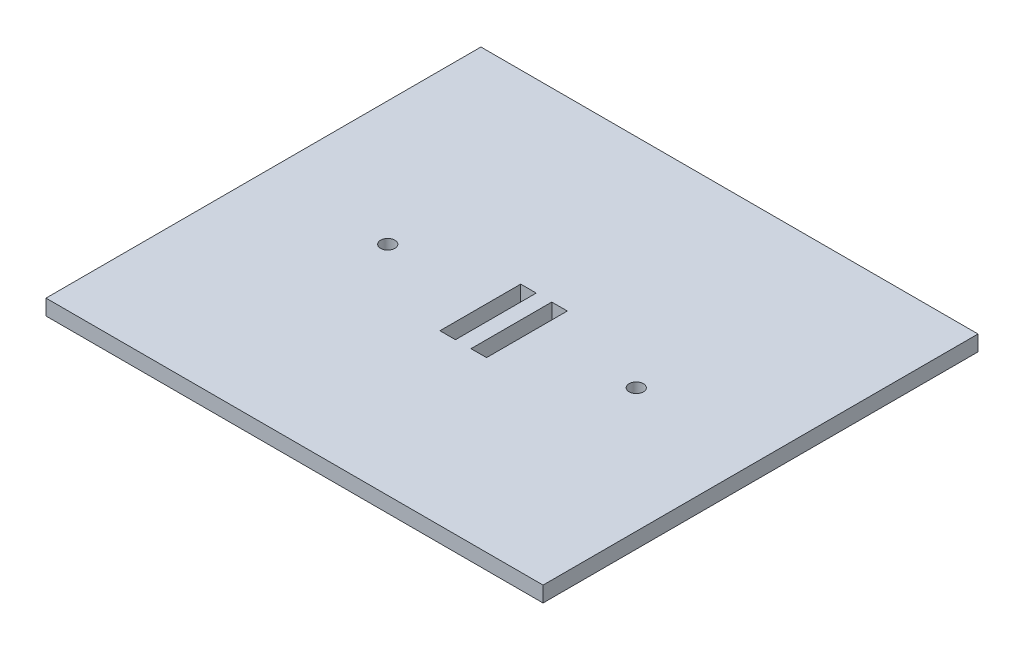
SolidWorks part; units mm, degrees
ref_plane "Front Plane" through (0, 0, 0) normal (0, 0, 1) x (1, 0, 0)
ref_plane "Top Plane" through (0, 0, 0) normal (0, 1, 0) x (1, 0, 0)
ref_plane "Right Plane" through (0, 0, 0) normal (1, 0, 0) x (0, 0, -1)
sketch "Sketch2" plane through (0, 0, 0) normal (0, 1, 0) x (1, 0, 0)
  line L2 (-50.8, -44.45) -> (50.8, -44.45)
  line L3 (-50.8, -44.45) -> (-50.8, 44.45)
  line L4 (-50.8, 44.45) -> (50.8, 44.45)
  line L5 (50.8, -44.45) -> (50.8, 44.45)
  line L6 (-50.8, -44.45) -> (50.8, 44.45) construction
  line L7 (-50.8, 44.45) -> (50.8, -44.45) construction
  point P1 (0, 0)
  dimension "D1" = 101.6
  dimension "D2" = 88.9
extrude "Boss-Extrude1" add sketch "Sketch2" along normal blind 3.175
sketch "Sketch3" plane through (0, 3.175, 0) normal (0, 1, 0) x (1, 0, 0)
  line L0 (-50.8, 44.45) -> (-50.8, -44.45) construction
  circle A0 centre (-25.4, 0) radius 1.4605
  circle A1 centre (25.4, 0) radius 1.4605
  dimension "D1" = 2.921
  dimension "D2" = 2.921
  dimension "D3" = 50.8
  dimension "D4" = 25.4
extrude "Cut-Extrude1" cut sketch "Sketch3" against normal through all
sketch "Sketch5" plane through (0, 3.175, 0) normal (0, 1, 0) x (1, 0, 0)
  line L0 (-1.5875, 6.5412) -> (-1.5875, -9.9688)
  line L1 (-1.5875, 6.5412) -> (-4.7625, 6.5412)
  line L2 (-4.7625, 6.5412) -> (-4.7625, -9.9688)
  line L3 (-4.7625, -9.9688) -> (-1.5875, -9.9688)
  line L5 (0, 44.45) -> (0, -26.5927) construction
  line L6 (50.8, 44.45) -> (-50.8, 44.45) construction
  line L7 (4.7625, 6.5412) -> (4.7625, -9.9688)
  line L8 (1.5875, 6.5412) -> (4.7625, 6.5412)
  line L9 (1.5875, 6.5412) -> (1.5875, -9.9688)
  line L10 (4.7625, -9.9688) -> (1.5875, -9.9688)
  dimension "D1" = 3.175
  dimension "D2" = 16.51
  dimension "D3" = 1.5875
extrude "Cut-Extrude2" cut sketch "Sketch5" against normal through all
